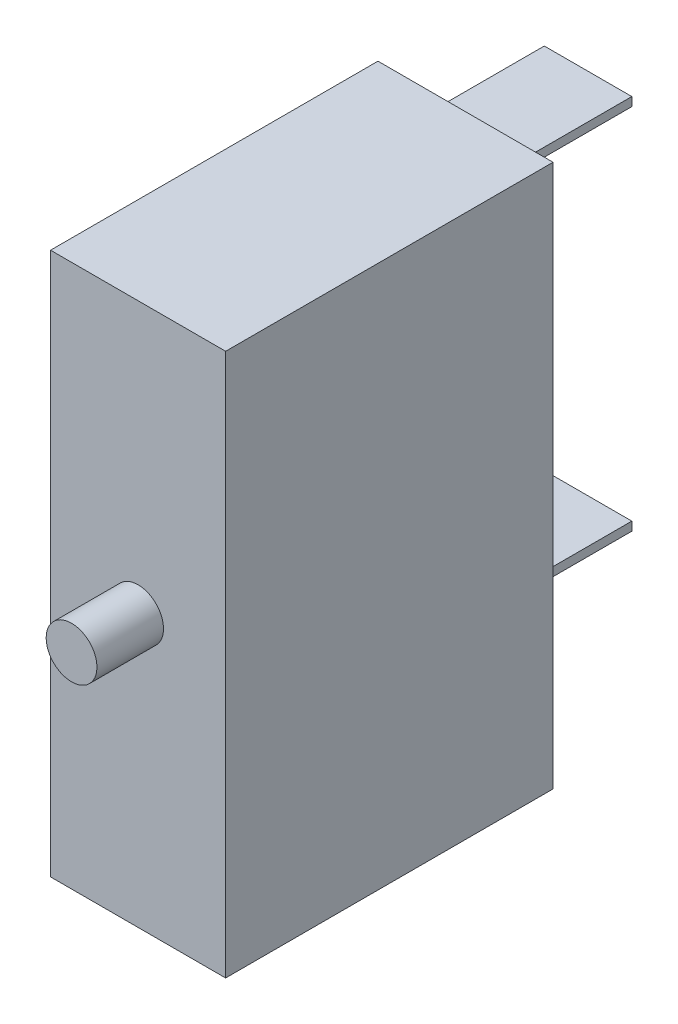
SolidWorks part; units mm, degrees
ref_plane "Front" through (0, 0, 0) normal (0, 0, 1) x (1, 0, 0)
ref_plane "Top" through (0, 0, 0) normal (0, 1, 0) x (1, 0, 0)
ref_plane "Right" through (0, 0, 0) normal (1, 0, 0) x (0, 0, -1)
ref_plane "Plane1" through (5, 0, 0) normal (1, 0, 0) x (0, 0, -1)
sketch "Sketch1" plane through (5, 0, 0) normal (1, 0, 0) x (0, 0, -1)
  line L0 (18, -23) -> (18, 23)
  line L1 (18, 23) -> (-0.7, 23)
  line L2 (-0.7, 23) -> (-0.7, -23)
  line L3 (-0.7, -23) -> (18, -23)
extrude "Boss-Extrude1" add sketch "Sketch1" against normal blind 10
sketch "Sketch2" plane through (-5, 0, 0) normal (-1, 0, 0) x (0, 0, 1)
  line L0 (-18, -23) -> (0, -23)
  line L1 (0, -23) -> (0, -15.5)
  line L2 (0, -15.5) -> (-18, -15.5)
  line L3 (-18, -15.5) -> (-18, -23)
extrude "Cut-Extrude1" cut sketch "Sketch2" against normal through all
sketch "Sketch3" plane through (-5, 0, 0) normal (-1, 0, 0) x (0, 0, 1)
  line L0 (-18, 15.5) -> (0, 15.5)
  line L1 (0, 15.5) -> (0, 23)
  line L2 (0, 23) -> (-18, 23)
  line L3 (-18, 23) -> (-18, 15.5)
extrude "Cut-Extrude2" cut sketch "Sketch3" against normal through all
sketch "Sketch4" plane through (0, 0, -18) normal (0, 0, -1) x (-1, 0, 0)
  line L0 (-2.5, -7) -> (2.5, -7)
  line L1 (2.5, -7) -> (2.5, -7.5)
  line L2 (2.5, -7.5) -> (-2.5, -7.5)
  line L3 (-2.5, -7.5) -> (-2.5, -7)
  line L4 (-5, -15.5) -> (5, -15.5) construction
  point P6 (0, -7.5)
  dimension "D1" = 8
  dimension "D2" = 0.5
  dimension "D3" = 5
extrude "Boss-Extrude2" add sketch "Sketch4" along normal blind 7
sketch "Sketch5" plane through (0, 0, -18) normal (0, 0, -1) x (-1, 0, 0)
  line L0 (-2.5, 14) -> (2.5, 14)
  line L1 (2.5, 14) -> (2.5, 13.5)
  line L2 (2.5, 13.5) -> (-2.5, 13.5)
  line L3 (-2.5, 13.5) -> (-2.5, 14)
  line L4 (-5, 15.5) -> (5, 15.5) construction
  point P6 (0, 13.5)
  dimension "D1" = 1.5
  dimension "D2" = 5
  dimension "D3" = 0.5
extrude "Boss-Extrude3" add sketch "Sketch5" along normal blind 7
ref_plane "Plane2" through (0, 0, 0) normal (0, -1, 0) x (1, 0, 0)
sketch "Sketch6" plane through (0, 0, 0) normal (0, -1, 0) x (1, 0, 0)
  line L0 (1.45, 4.5) -> (0, 4.5)
  line L1 (0, 4.5) -> (0, 0.7)
  line L2 (0, 0.7) -> (1.45, 0.7)
  line L3 (1.45, 0.7) -> (1.45, 4.5)
  line L4 (0, 4.5) -> (0, 0.7) construction
revolve "Revolve1" add sketch "Sketch6" angle 360 about L4
hole_wizard "Ø2.5 (2.5) Diameter Hole1" positions "Sketch8" profile "Sketch7" hole size "Ø2.5" standard "ANSI Metric"
sketch "Sketch8" plane through (0, 0, 0.7) normal (0, 0, 1) x (1, 0, 0)
  line L0 (0, 21) -> (0, -21) construction
  point P0 (0, -21)
  point P1 (0, 21)
  dimension "D1" = 42
sketch "Sketch7" plane through (0, -21, 0.7) normal (1, 0, 0) x (0, -1, 0)
  line L0 (0, 0) -> (0, 25.7)
  line L1 (0, 25.7) -> (1.25, 25.7)
  line L2 (1.25, 25.7) -> (1.25, 0)
  line L5 (1.25, 0) -> (0, 0)
  line L11 (0, -6.35) -> (0, 107.95) construction
  dimension "Thru Hole Dia." = 2.5
  dimension "Thru Hole Depth" = 25.7
fillet "Fillet1" radius 0.5 4 edges at (5, 23, 0.35) (-5, 23, 0.35) (-5, -23, 0.35) (5, -23, 0.35)
sketch "Sketch9" plane through (0, 0, 0) normal (0, 0, -1) x (-1, 0, 0)
  line L4 (4.5, 23) -> (-4.5, 23)
  line L5 (-5, 22.5) -> (-5, 15.5)
  line L6 (-5, 15.5) -> (5, 15.5)
  line L7 (5, 15.5) -> (5, 22.5)
  line L8 (4.5, 23) -> (-4.5, 23)
  line L9 (-5, 22.5) -> (-5, 15.5)
  line L10 (-5, 15.5) -> (5, 15.5)
  line L11 (5, 15.5) -> (5, 22.5)
  line L12 (-4.5, -23) -> (4.5, -23)
  line L13 (5, -22.5) -> (5, -15.5)
  line L14 (5, -15.5) -> (-5, -15.5)
  line L15 (-5, -15.5) -> (-5, -22.5)
  line L16 (-4.5, -23) -> (4.5, -23)
  line L17 (5, -22.5) -> (5, -15.5)
  line L18 (5, -15.5) -> (-5, -15.5)
  line L19 (-5, -15.5) -> (-5, -22.5)
  arc A2 (-4.5, 23) -> (-5, 22.5) centre (-4.5, 22.5) ccw
  arc A3 (5, 22.5) -> (4.5, 23) centre (4.5, 22.5) ccw
  arc A4 (-4.5, 23) -> (-5, 22.5) centre (-4.5, 22.5) ccw
  arc A5 (5, 22.5) -> (4.5, 23) centre (4.5, 22.5) ccw
  arc A6 (4.5, -23) -> (5, -22.5) centre (4.5, -22.5) ccw
  arc A7 (-5, -22.5) -> (-4.5, -23) centre (-4.5, -22.5) ccw
  arc A8 (4.5, -23) -> (5, -22.5) centre (4.5, -22.5) ccw
  arc A9 (-5, -22.5) -> (-4.5, -23) centre (-4.5, -22.5) ccw
  dimension "D1" = 0
  dimension "D2" = 0
extrude "Cut-Extrude3" cut sketch "Sketch9" against normal through all both and the other way through all
